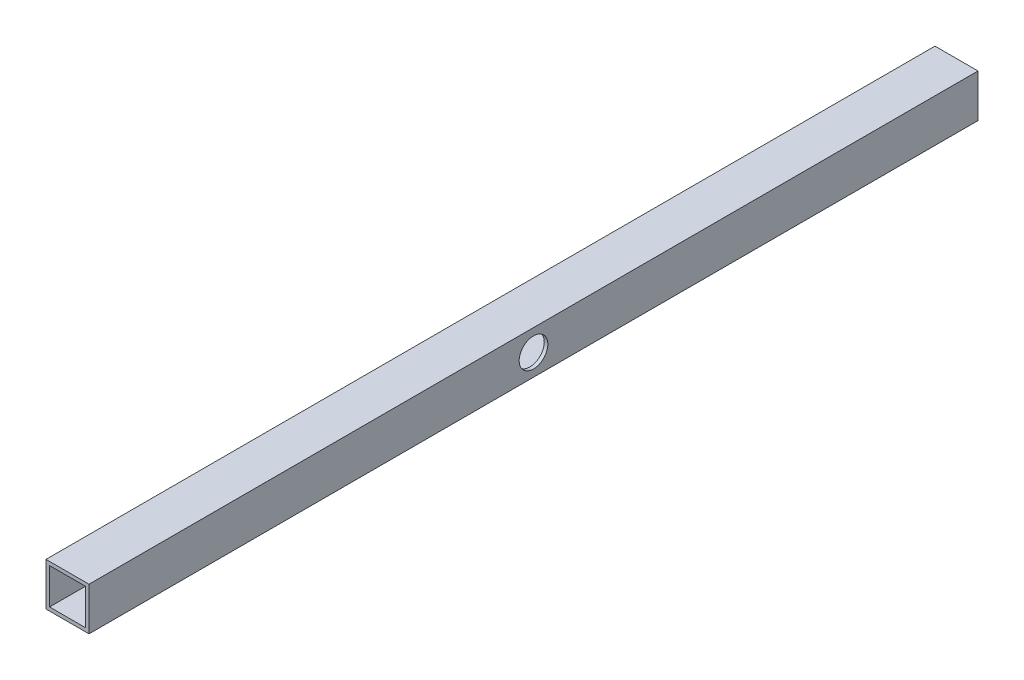
SolidWorks part; units mm, degrees
material "6061 Alloy"
ref_plane "Front Plane" through (0, 0, 0) normal (0, 0, 1) x (1, 0, 0)
ref_plane "Top Plane" through (0, 0, 0) normal (0, 1, 0) x (1, 0, 0)
ref_plane "Right Plane" through (0, 0, 0) normal (1, 0, 0) x (0, 0, -1)
sketch "Sketch1" plane through (0, 0, 0) normal (0, 0, 1) x (1, 0, 0)
  line L1 (-7.9375, -7.9375) -> (7.9375, -7.9375)
  line L2 (-7.9375, -7.9375) -> (-7.9375, 7.9375)
  line L3 (-7.9375, 7.9375) -> (7.9375, 7.9375)
  line L4 (7.9375, -7.9375) -> (7.9375, 7.9375)
  line L5 (-7.9375, -7.9375) -> (7.9375, 7.9375) construction
  line L6 (-7.9375, 7.9375) -> (7.9375, -7.9375) construction
  line L7 (-9.525, -9.525) -> (9.525, -9.525)
  line L8 (-9.525, -9.525) -> (-9.525, 9.525)
  line L9 (-9.525, 9.525) -> (9.525, 9.525)
  line L10 (9.525, -9.525) -> (9.525, 9.525)
  line L11 (-9.525, -9.525) -> (9.525, 9.525) construction
  line L12 (-9.525, 9.525) -> (9.525, -9.525) construction
  point P0 (0, 0)
  point P6 (0, 0)
  dimension "D1" = 19.05
  dimension "D2" = 19.05
  dimension "D3" = 1.5875
  dimension "D4" = 1.5875
extrude "Boss-Extrude1" add sketch "Sketch1" along normal mid plane 393.7
sketch "Sketch2" plane through (0, 0, 0) normal (1, 0, 0) x (0, 0, -1)
  circle A0 centre (0, 0) radius 6.35
extrude "Cut-Extrude1" cut sketch "Sketch2" against normal through all both and the other way through all
